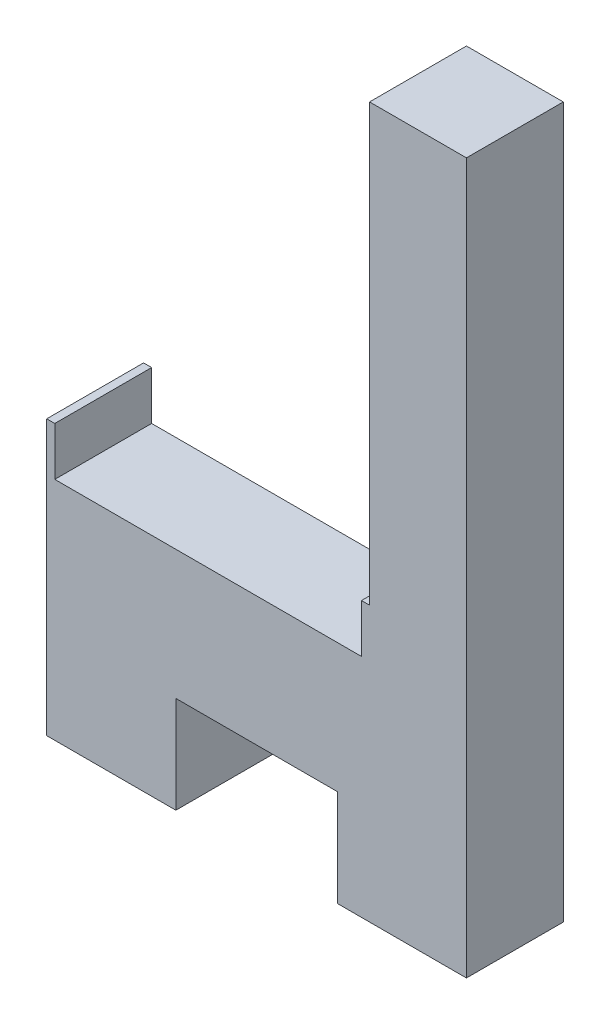
SolidWorks part; units mm, degrees
ref_plane "Plan de face" through (0, 0, 0) normal (0, 0, 1) x (1, 0, 0)
ref_plane "Plan de dessus" through (0, 0, 0) normal (0, 1, 0) x (1, 0, 0)
ref_plane "Plan de droite" through (0, 0, 0) normal (1, 0, 0) x (0, 0, -1)
sketch "Esquisse1" plane through (0, 0, 0) normal (0, 0, 1) x (1, 0, 0)
  line L0 (13, -22) -> (13, 22)
  line L1 (13, 22) -> (7, 22)
  line L2 (7, 22) -> (7, -5)
  line L3 (7, -5) -> (6.5, -5)
  line L4 (6.5, -5) -> (6.5, -8)
  line L5 (6.5, -8) -> (-12.5, -8)
  line L6 (-12.5, -8) -> (-12.5, -5)
  line L7 (-12.5, -5) -> (-13, -5)
  line L8 (-13, -22) -> (-5, -22)
  line L9 (-5, -22) -> (-5, -16)
  line L10 (-5, -16) -> (5, -16)
  line L11 (5, -16) -> (5, -22)
  line L12 (5, -22) -> (13, -22)
  line L13 (-13, -5) -> (-13, -22)
  dimension "D1" = 19
  dimension "D2" = 8
  dimension "D3" = 6
  dimension "D4" = 3
  dimension "D5" = 8
  dimension "D6" = 20
extrude "Boss.-Extru.1" add sketch "Esquisse1" along normal blind 6
